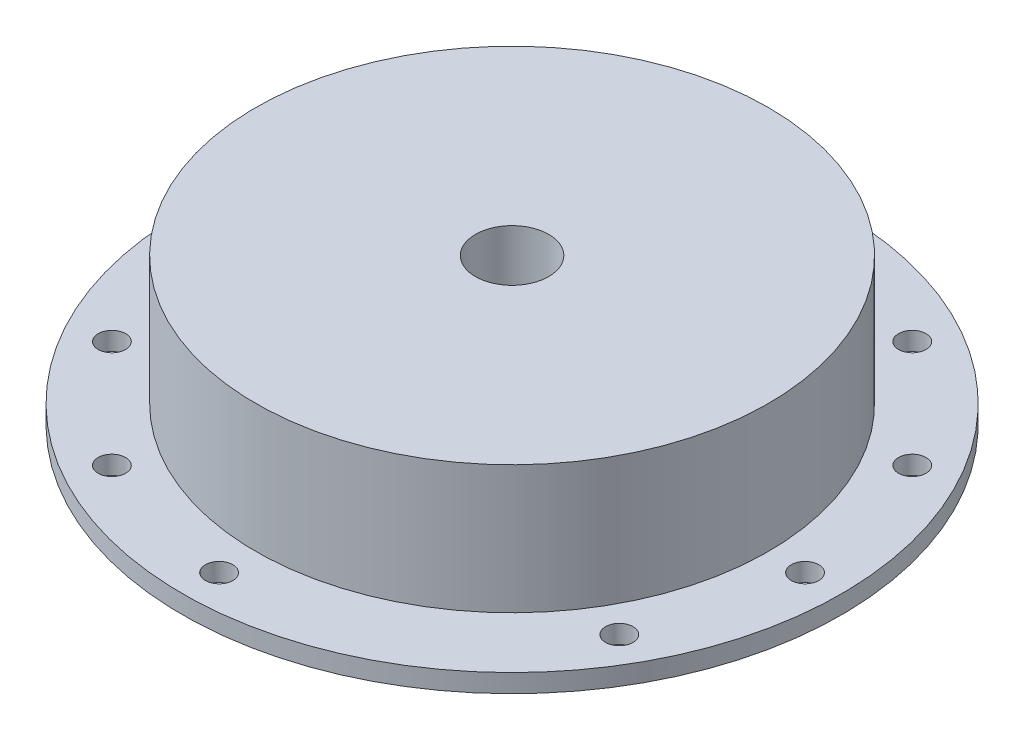
SolidWorks part; units mm, degrees
ref_plane "Front Plane" through (0, 0, 0) normal (0, 0, 1) x (1, 0, 0)
ref_plane "Top Plane" through (0, 0, 0) normal (0, 1, 0) x (1, 0, 0)
ref_plane "Right Plane" through (0, 0, 0) normal (1, 0, 0) x (0, 0, -1)
sketch "Sketch1" plane through (0, 0, 0) normal (0, 0, 1) x (1, 0, 0)
  line L0 (12.7, 50.8) -> (12.7, 25.4)
  line L1 (63.5, 0) -> (114.3, 0)
  line L2 (114.3, 0) -> (114.3, 6.35)
  line L3 (114.3, 6.35) -> (88.9, 6.35)
  line L4 (88.9, 6.35) -> (88.9, 50.8)
  line L5 (88.9, 50.8) -> (12.7, 50.8)
  line L6 (0, 0) -> (0, 33.4189) construction
  arc A0 (12.7, 25.4) -> (63.5, 0) centre (63.5, 63.5) ccw
  point P11 (42.3796, 0)
  point P12 (33.4988, 0)
  point P13 (0, 0)
  point P14 (70.1733, 0)
  point P15 (6.35, 22.9759)
  dimension "D1" = 25.4
  dimension "D2" = 228.6
  dimension "D3" = 25.4
  dimension "D4" = 6.35
  dimension "D5" = 50.8
  dimension "D6" = 127
  dimension "D7" = 25.4
revolve "Revolve1" add sketch "Sketch1" angle 360 about L6
sketch "Sketch3" plane through (0, 6.35, 0) normal (0, 1, 0) x (1, 0, 0)
  line L0 (0, 0) -> (0, -101.6) construction
  point P4 (0, -101.6)
  dimension "D1" = 101.6
hole_wizard "3/8 (0.375) Diameter Hole2" positions "Sketch4" profile "Sketch5" hole size "3/8" standard "ANSI Inch" end condition through all
sketch "Sketch4" plane through (0, 6.35, 0) normal (0, 1, 0) x (1, 0, 0)
  point P0 (0, -101.6)
sketch "Sketch5" plane through (0, 6.35, 101.6) normal (1, 0, 0) x (0, 0, 1)
  line L0 (0, 0) -> (0, 6.35)
  line L1 (0, 6.35) -> (4.7625, 6.35)
  line L2 (4.7625, 6.35) -> (4.7625, 0)
  line L5 (4.7625, 0) -> (0, 0)
  line L11 (0, -6.35) -> (0, 107.95) construction
  dimension "Thru Hole Dia." = 9.525
  dimension "Thru Hole Depth" = 6.35
pattern_circular "CirPattern2" count 12 over 360 about axis through (0, 0, 0) along (0, -1, 0) skipping 1 of "3/8 (0.375) Diameter Hole2"
